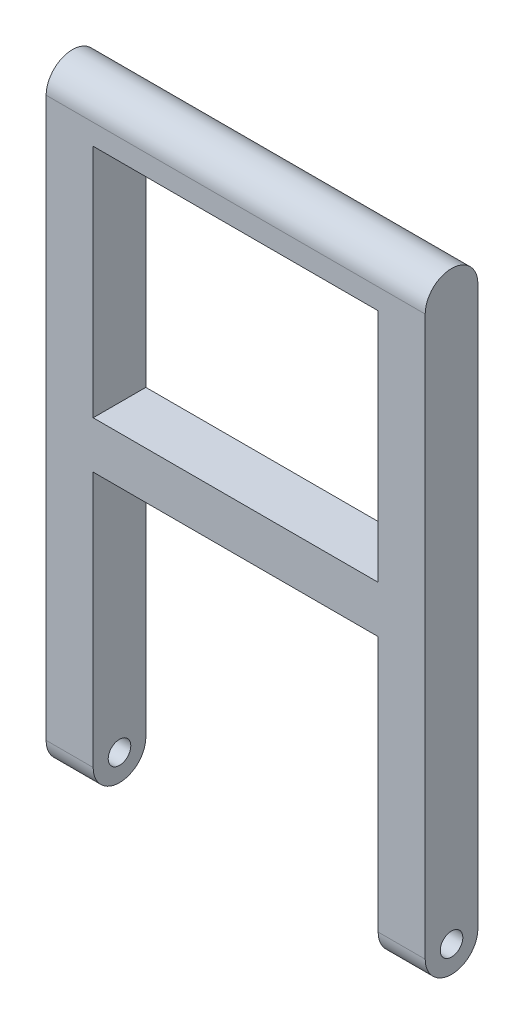
SolidWorks part; units mm, degrees
ref_plane "Přední rovina" through (0, 0, 0) normal (0, 0, 1) x (1, 0, 0)
ref_plane "Horní rovina" through (0, 0, 0) normal (0, 1, 0) x (1, 0, 0)
ref_plane "Pravá rovina" through (0, 0, 0) normal (1, 0, 0) x (0, 0, -1)
sketch "Skica1" plane through (0, 0, 0) normal (0, 0, 1) x (1, 0, 0)
  line L0 (0, 0) -> (0, 65)
  line L1 (0, 65) -> (40.3, 65)
  line L2 (40.3, 65) -> (40.3, 0)
  line L3 (40.3, 0) -> (35.3, 0)
  line L4 (35.3, 0) -> (35.3, 60)
  line L5 (35.3, 60) -> (5, 60)
  line L6 (5, 60) -> (5, 0)
  line L7 (5, 0) -> (0, 0)
  line L9 (5, 35) -> (35.3, 35)
  line L10 (5, 35) -> (5, 30)
  line L11 (5, 30) -> (35.3, 30)
  line L12 (35.3, 35) -> (35.3, 30)
  dimension "D1" = 5
  dimension "D2" = 5
  dimension "D3" = 5
  dimension "D4" = 5
  dimension "D5" = 40.3
  dimension "D6" = 65
extrude "Přidat vysunutím1" add sketch "Skica1" along normal blind 5.6 contours L7 L6 L5 L4 L3 L2 L1 L0 | L6 L11 L4 L9
sketch "Skica2" plane through (0, 0, 0) normal (-1, 0, 0) x (0, 0, 1)
  line L0 (5.6, 2.8) -> (5.6, 0)
  line L1 (5.6, 0) -> (0, 0)
  line L2 (0, 0) -> (0, 2.8)
  circle A0 centre (2.8, 2.8) radius 2.8
  circle A1 centre (2.8, 2.8) radius 1.2
  line M2 (0, 65) -> (0, 0)
  line M3 (0, 0) -> (5.6, 0)
  line M4 (5.6, 0) -> (5.6, 65)
  dimension "D1" = 2.4
extrude "Odebrat vysunutím1" cut sketch "Skica2" against normal through all contours A0 L1 M4 | A0 M2 M3 | A1
sketch "Skica3" plane through (0, 0, 0) normal (-1, 0, 0) x (0, 0, 1)
  line L0 (5.6, 62.2) -> (5.6, 65)
  line L1 (5.6, 65) -> (0, 65)
  line L2 (0, 65) -> (0, 62.2)
  circle A0 centre (2.8, 62.2) radius 2.8
extrude "Odebrat vysunutím3" cut sketch "Skica3" against normal through all
